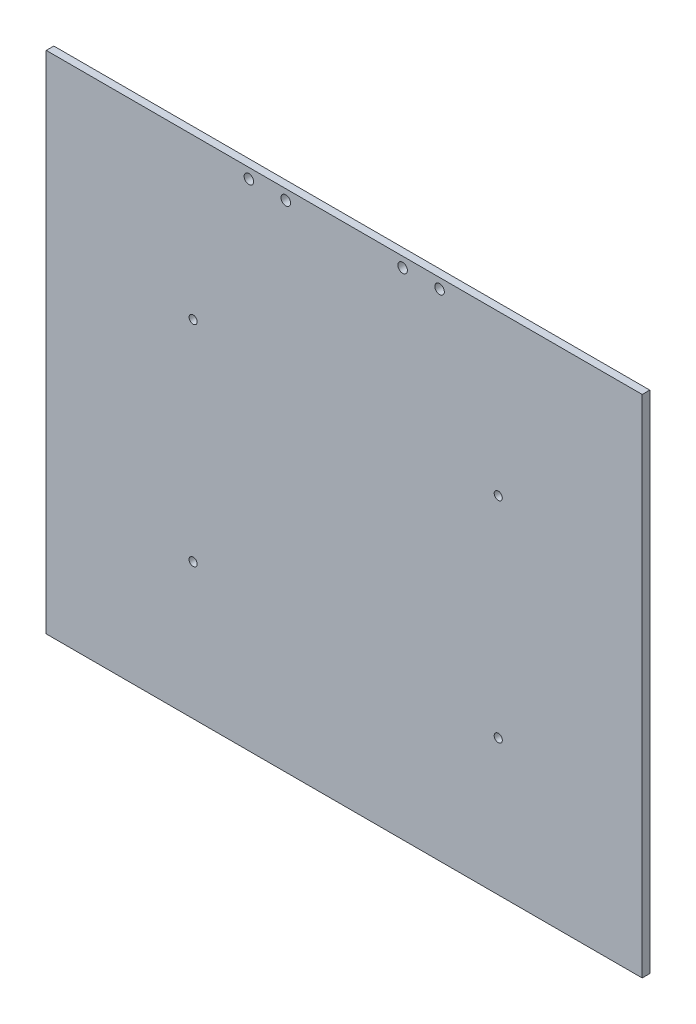
SolidWorks part; units mm, degrees
ref_plane "Front" through (0, 0, 0) normal (0, 0, 1) x (1, 0, 0)
ref_plane "Top" through (0, 0, 0) normal (0, 1, 0) x (1, 0, 0)
ref_plane "Right" through (0, 0, 0) normal (1, 0, 0) x (0, 0, -1)
sketch "Sketch1" plane through (0, 0, 0) normal (0, 0, 1) x (1, 0, 0)
  line L1 (-219.7176, 192.2822) -> (30.2824, 192.2822)
  line L2 (-219.7176, 192.2822) -> (-219.7176, -19.7178)
  line L3 (-219.7176, -19.7178) -> (30.2824, -19.7178)
  line L4 (30.2824, 192.2822) -> (30.2824, -19.7178)
  circle A0 centre (-158.1043, 37.3108) radius 1.7 construction
  circle A1 centre (-158.1043, 37.3108) radius 1.7
  circle A2 centre (-30.1043, 37.3108) radius 1.7 construction
  circle A3 centre (-30.1043, 37.3108) radius 1.7
  circle A4 centre (-158.1043, 125.3108) radius 1.7 construction
  circle A5 centre (-30.1043, 125.3108) radius 1.7 construction
  circle A6 centre (-158.1043, 125.3108) radius 1.7
  circle A7 centre (-30.1043, 125.3108) radius 1.7
  circle A8 centre (-54.7176, 188.0514) radius 2 construction
  circle A9 centre (-70.2176, 188.0514) radius 2 construction
  circle A10 centre (-119.2176, 188.0514) radius 2 construction
  circle A11 centre (-134.7176, 188.0514) radius 2 construction
  circle A12 centre (-54.7176, 188.0514) radius 2
  circle A13 centre (-70.2176, 188.0514) radius 2
  circle A14 centre (-119.2176, 188.0514) radius 2
  circle A15 centre (-134.7176, 188.0514) radius 2
  dimension "D1" = 250
  dimension "D2" = 212
extrude "Boss-Extrude1" add sketch "Sketch1" along normal blind 3.175
